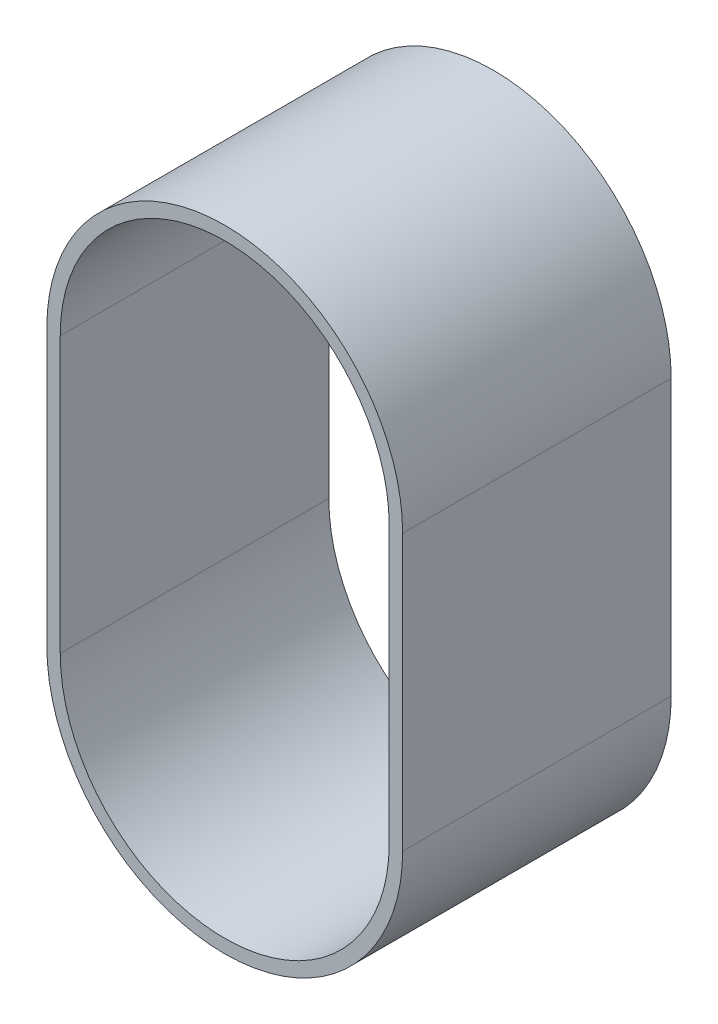
SolidWorks part; units mm, degrees
ref_plane "Front Plane" through (0, 0, 0) normal (0, 0, 1) x (1, 0, 0)
ref_plane "Top Plane" through (0, 0, 0) normal (0, 1, 0) x (1, 0, 0)
ref_plane "Right Plane" through (0, 0, 0) normal (1, 0, 0) x (0, 0, -1)
sketch "Sketch1" plane through (0, 0, 0) normal (0, 0, 1) x (1, 0, 0)
  line L0 (-2.8862, -28.7867) -> (-2.8862, 49971.2133) construction
  line L4 (-15.3862, -16.2867) -> (49984.6138, -16.2867) construction
  line L6 (-2.8862, -6.0367) -> (-2.8862, -26.5367) construction
  line L7 (10.3638, -6.0367) -> (10.3638, -26.5367)
  line L8 (-16.1362, -6.0367) -> (-16.1362, -26.5367)
  line L13 (9.3638, -6.0367) -> (9.3638, -26.5367)
  line L14 (-15.1362, -6.0367) -> (-15.1362, -26.5367)
  arc A0 (10.3638, -6.0367) -> (-16.1362, -6.0367) centre (-2.8862, -6.0367) ccw
  arc A1 (-16.1362, -26.5367) -> (10.3638, -26.5367) centre (-2.8862, -26.5367) ccw
  arc A4 (-15.1362, -26.5367) -> (9.3638, -26.5367) centre (-2.8862, -26.5367) ccw
  arc A5 (9.3638, -6.0367) -> (-15.1362, -6.0367) centre (-2.8862, -6.0367) ccw
  point P12 (-2.8862, -16.2867)
  dimension "D1" = 1
extrude "Boss-Extrude1" add sketch "Sketch1" along normal blind 20
